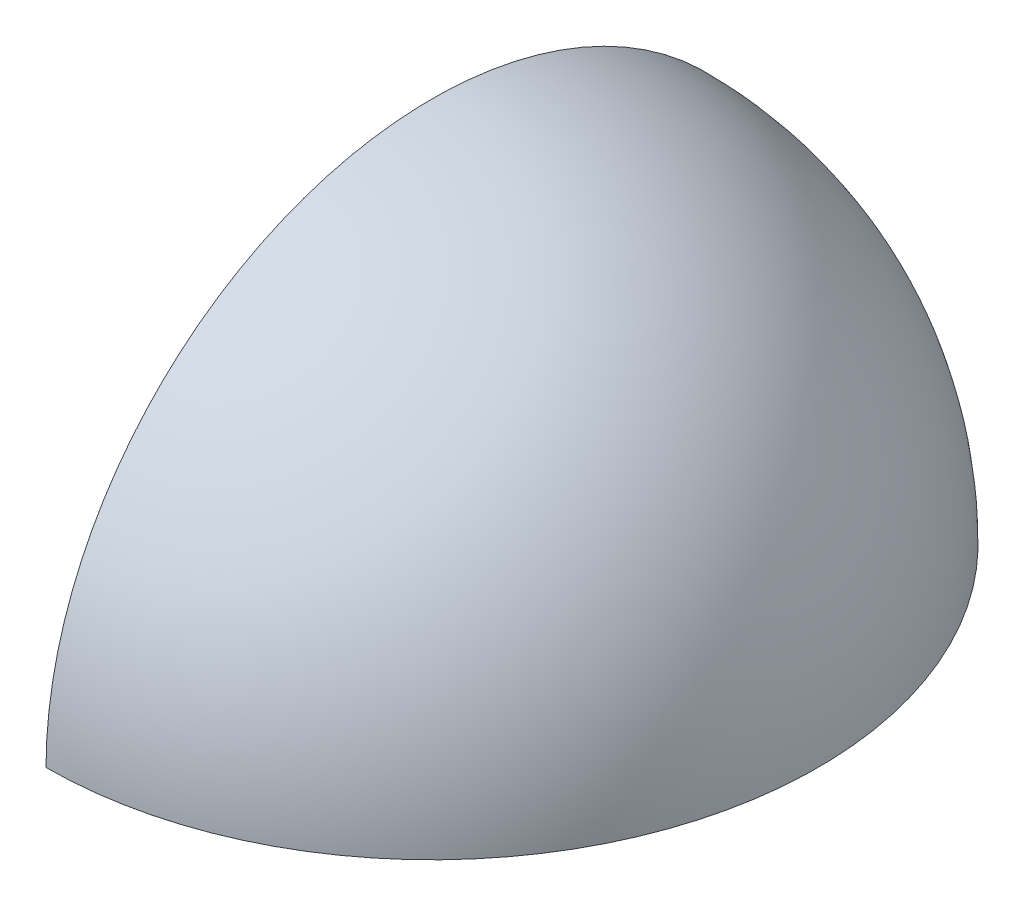
SolidWorks part; units mm, degrees
ref_plane "Front Plane" through (0, 0, 0) normal (0, 0, 1) x (1, 0, 0)
ref_plane "Top Plane" through (0, 0, 0) normal (0, 1, 0) x (1, 0, 0)
ref_plane "Right Plane" through (0, 0, 0) normal (1, 0, 0) x (0, 0, -1)
sketch "Sketch1" plane through (0, 0, 0) normal (0, 1, 0) x (1, 0, 0)
  line L0 (0, 55.3005) -> (0, -68.1373) construction
  line L1 (0, 19.05) -> (0, -19.05)
  arc A0 (0, 19.05) -> (0, -19.05) centre (0, 0) cw
revolve "Revolve1" add sketch "Sketch1" angle 90 about L1
